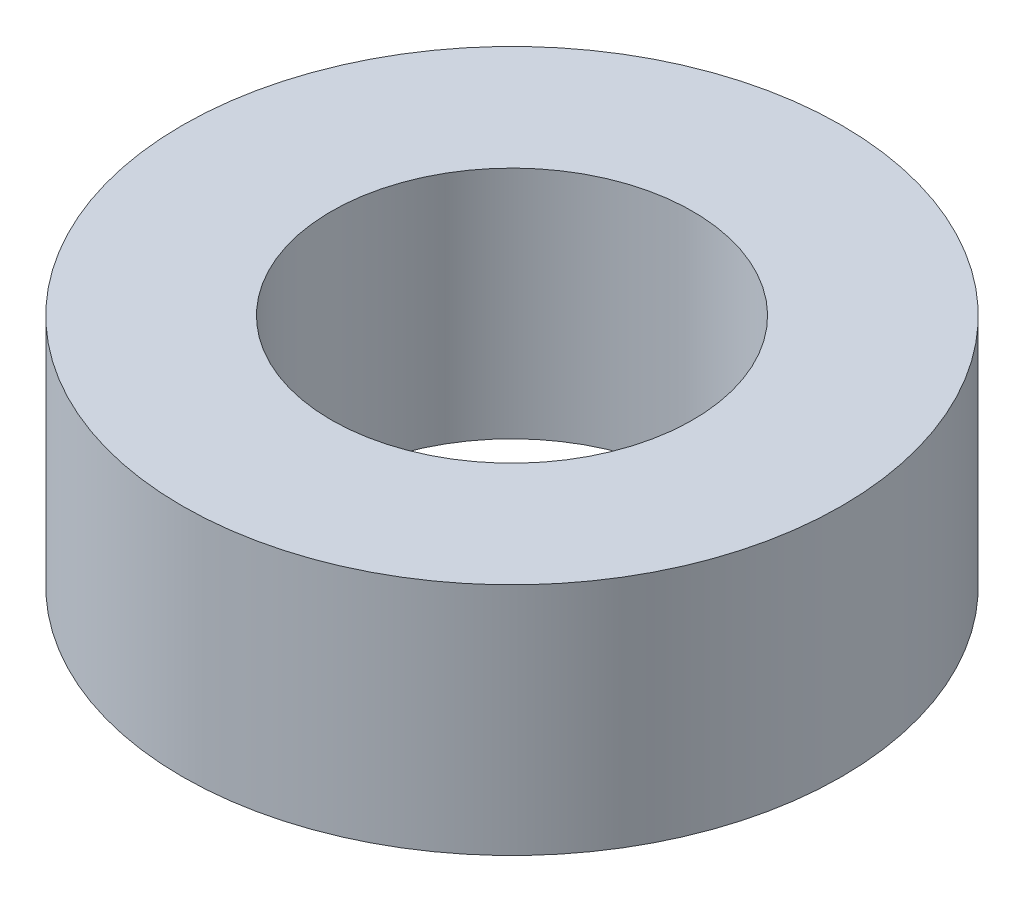
SolidWorks part; units mm, degrees
ref_plane "Front Plane" through (0, 0, 0) normal (0, 0, 1) x (1, 0, 0)
ref_plane "Top Plane" through (0, 0, 0) normal (0, 1, 0) x (1, 0, 0)
ref_plane "Right Plane" through (0, 0, 0) normal (1, 0, 0) x (0, 0, -1)
sketch "Sketch1" plane through (0, 0, 0) normal (0, 1, 0) x (1, 0, 0)
  circle A0 centre (0, 0) radius 3.7
  circle A1 centre (0, 0) radius 6.75
  dimension "D1" = 7.4
  dimension "D2" = 13.5
extrude "Boss-Extrude1" add sketch "Sketch1" along normal blind 4.8
